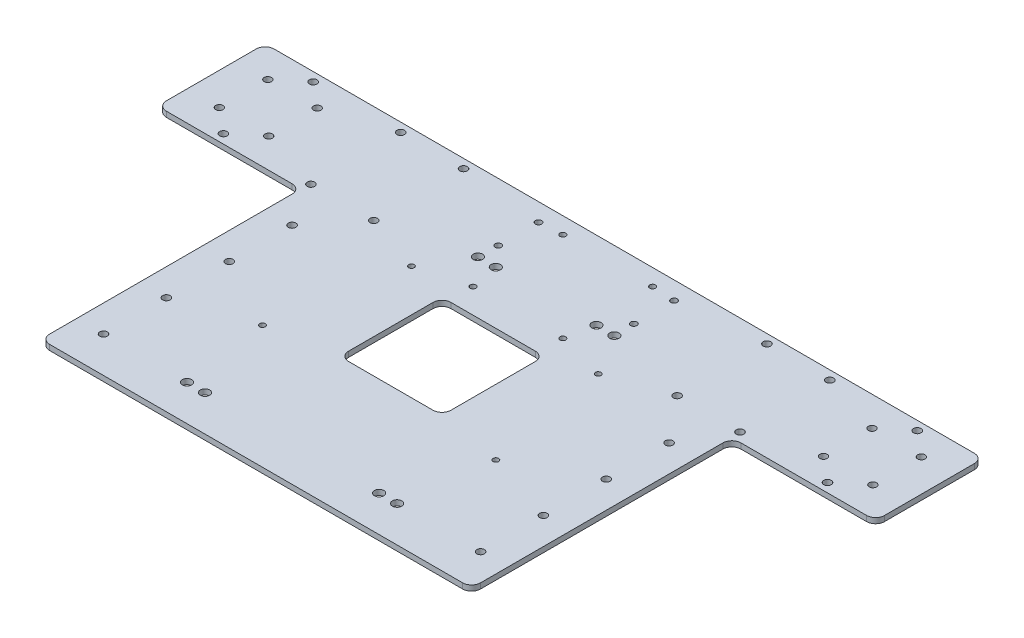
SolidWorks part; units mm, degrees
material "Thornel Mat VMA"
ref_plane "前视基准面" through (0, 0, 0) normal (0, 0, 1) x (1, 0, 0)
ref_plane "上视基准面" through (0, 0, 0) normal (0, 1, 0) x (1, 0, 0)
ref_plane "右视基准面" through (0, 0, 0) normal (1, 0, 0) x (0, 0, -1)
sketch "草图1" plane through (0, 0, 0) normal (0, 1, 0) x (1, 0, 0)
  line L0 (0, -205) -> (0, 0) construction
  line L1 (-200, -60) -> (200, -60)
  line L2 (-200, -60) -> (-200, 0)
  line L3 (-200, 0) -> (200, 0)
  line L4 (200, -60) -> (200, 0)
  line L6 (25, -59.2) -> (-25, -59.2) construction
  line L7 (-120, -205) -> (120, -205)
  line L8 (-120, -205) -> (-120, -60)
  line L9 (-120, -60) -> (120, -60)
  line L10 (120, -205) -> (120, -60)
  line L11 (25, -59.2) -> (25, -9.2) construction
  line L12 (25, -9.2) -> (-25, -9.2) construction
  line L13 (-25, -59.2) -> (-25, -9.2) construction
  line L14 (25, -59.2) -> (-25, -9.2) construction
  line L15 (25, -9.2) -> (-25, -59.2) construction
  line L16 (-28.5, -101.5) -> (28.5, -101.5) construction
  line L17 (-28.5, -73) -> (28.5, -73)
  line L18 (-28.5, -73) -> (-28.5, -130)
  line L19 (-28.5, -130) -> (28.5, -130)
  line L20 (28.5, -73) -> (28.5, -130)
  circle A0 centre (-25, -9.2) radius 1.6
  circle A1 centre (-25, -59.2) radius 1.6
  circle A2 centre (25, -9.2) radius 1.6
  circle A3 centre (25, -59.2) radius 1.6
  point P0 (0, 0)
  point P6 (0, -34.2)
  point P35 (0, -73)
  dimension "D8" = 50
  dimension "D6" = 3.2
  dimension "D1" = 400
  dimension "D2" = 60
  dimension "D3" = 145
  dimension "D4" = 240
  dimension "D5" = 13
  dimension "D7" = 50
  dimension "D9" = 9.2
  dimension "D12" = 57
extrude "构型与裁判孔" add sketch "草图1" along normal blind 3
sketch "草图2" plane through (0, 3, 0) normal (0, 1, 0) x (1, 0, 0)
  line L0 (-200, -30) -> (200, -30) construction
  line L1 (-200, -60) -> (-200, 0) construction
  line L2 (200, -60) -> (200, 0) construction
  line L3 (0, 0) -> (0, -205) construction
  line L4 (-200, 0) -> (200, 0) construction
  line L5 (-120, -205) -> (120, -205) construction
  line L6 (-182, -43.5) -> (-182, -16.5) construction
  line L7 (-154.5, -43.5) -> (-154.5, -16.5) construction
  line L8 (-182, -16.5) -> (-154.5, -16.5) construction
  line L9 (-84.5, -55) -> (-84.5, -5) construction
  line L10 (-168.25, -16.5) -> (-168.25, 0) construction
  line L11 (-168.25, -5) -> (-119.5, -5) construction
  circle A0 centre (-182, -16.5) radius 2.05
  circle A1 centre (-182, -43.5) radius 2.05
  circle A2 centre (-154.5, -16.5) radius 2.05
  circle A3 centre (-154.5, -43.5) radius 2.05
  circle A4 centre (-84.5, -5) radius 2.1
  circle A5 centre (-119.5, -5) radius 2.1
  circle A6 centre (-84.5, -55) radius 2.1
  circle A7 centre (-119.5, -55) radius 2.1
  circle A8 centre (-168.25, -5) radius 2.1
  circle A9 centre (-168.25, -55) radius 2.1
  circle A10 centre (168.25, -55) radius 2.1
  circle A11 centre (168.25, -5) radius 2.1
  circle A12 centre (119.5, -55) radius 2.1
  circle A13 centre (84.5, -55) radius 2.1
  circle A14 centre (119.5, -5) radius 2.1
  circle A15 centre (84.5, -5) radius 2.1
  circle A16 centre (154.5, -43.5) radius 2.05
  circle A17 centre (154.5, -16.5) radius 2.05
  circle A18 centre (182, -43.5) radius 2.05
  circle A19 centre (182, -16.5) radius 2.05
  point P15 (-182, -30)
  point P20 (-154.5, -30)
  point P25 (-84.5, -30)
  dimension "D2" = 4.1
  dimension "D4" = 5
  dimension "D5" = 4.2
  dimension "D7" = 2
  dimension "D8" = 18
  dimension "D1" = 27
  dimension "D3" = 45.5
  dimension "D6" = 70
extrude "切除-拉伸1" cut sketch "草图2" against normal through all
fillet "圆角1" radius 5 12 edges at (120, 1.5, 60) (-120, 1.5, 60) (200, 1.5, 0) (200, 1.5, 60) (120, 1.5, 205) (-120, 1.5, 205) (-200, 1.5, 0) (-200, 1.5, 60) (-28.5, 1.5, 130) (28.5, 1.5, 130) (28.5, 1.5, 73) (-28.5, 1.5, 73)
sketch "草图3" plane through (0, 3, 0) normal (0, 1, 0) x (1, 0, 0)
  line L0 (-125, -60) -> (125, -60) construction
  line L1 (-105, -60) -> (-105, -205) construction
  line L2 (-115, -205) -> (115, -205) construction
  line L3 (0, 0) -> (0, -205) construction
  line L4 (-195, 0) -> (195, 0) construction
  line L5 (-120, -200) -> (-120, -65) construction
  line L6 (7.0759, -101.5) -> (64.0759, -101.5) construction
  line L7 (154.5, -43.5) -> (-154.5, -43.5) construction
  line L8 (-52, -66.5) -> (-65, -66.5) construction
  line L9 (-84.5376, -60) -> (-84.5376, -205) construction
  line L10 (-115, -205) -> (115, -205) construction
  line L11 (-120, -200) -> (-120, -65) construction
  line L12 (-52, -66.5) -> (-52, -136.5) construction
  line L13 (-52, -136.5) -> (-65, -136.5) construction
  line L14 (-65, -66.5) -> (-65, -136.5) construction
  line L15 (-58.5, -136.5) -> (-58.5, -66.5) construction
  line L16 (-52, -101.5) -> (-65, -101.5) construction
  line L17 (-28.5, -78) -> (-28.5, -125) construction
  line L18 (-105, -185) -> (105, -185) construction
  circle A0 centre (-105, -80) radius 2.1
  circle A1 centre (-105, -115) radius 2.1
  circle A2 centre (-105, -150) radius 2.1
  circle A3 centre (-105, -185) radius 2.1
  circle A4 centre (105, -185) radius 2.1
  circle A5 centre (105, -150) radius 2.1
  circle A6 centre (105, -115) radius 2.1
  circle A7 centre (105, -80) radius 2.1
  circle A8 centre (-52, -66.5) radius 1.55
  circle A9 centre (-65, -136.5) radius 1.55
  circle A10 centre (65, -136.5) radius 1.55
  circle A11 centre (52, -66.5) radius 1.55
  circle A12 centre (-38, -43.5) radius 2.6
  circle A13 centre (-28, -43.5) radius 2.6
  circle A14 centre (28, -43.5) radius 2.6
  circle A15 centre (38, -43.5) radius 2.6
  circle A16 centre (-58.5, -185) radius 2.6
  circle A17 centre (-48.5, -185) radius 2.6
  circle A18 centre (48.5, -185) radius 2.6
  circle A19 centre (58.5, -185) radius 2.6
  point P44 (-28.5, -101.5)
  point P495 (-58.5, -101.5)
  dimension "D1" = 20
  dimension "D2" = 35
  dimension "D3" = 35
  dimension "D4" = 35
  dimension "D7" = 3.1
  dimension "D10" = 5.2
  dimension "D11" = 10
  dimension "D12" = 28
  dimension "D14" = 10
  dimension "D5" = 15
  dimension "D6" = 35.4624
  dimension "D8" = 13
  dimension "D9" = 70
  dimension "D13" = 20
  dimension "D15" = 40
extrude "切除-拉伸2" cut sketch "草图3" against normal through all
sketch "草图4" plane through (0, 3, 0) normal (0, 1, 0) x (1, 0, 0)
  line L0 (0, -73) -> (0, 119.4643) construction
  line L1 (-23.5, -73) -> (23.5, -73) construction
  line L2 (-37.75, -10) -> (37.75, -10)
  line L3 (-195, 0) -> (195, 0) construction
  line L4 (-37.75, -10) -> (-37.75, -32.4) construction
  circle A0 centre (-37.75, -10) radius 1.75
  circle A1 centre (37.75, -10) radius 1.75
  circle A2 centre (-37.75, -32.4) radius 1.75
  circle A3 centre (37.75, -32.4) radius 1.75
  point P7 (0, -10)
  dimension "D3" = 3.5
  dimension "D4" = 3.5
  dimension "D6" = 3.5
  dimension "D1" = 75.5
  dimension "D2" = 10
  dimension "D5" = 22.4
extrude "切除-拉伸3" cut sketch "草图4" against normal blind 10 contours A0 | A2 | A1 | A3
